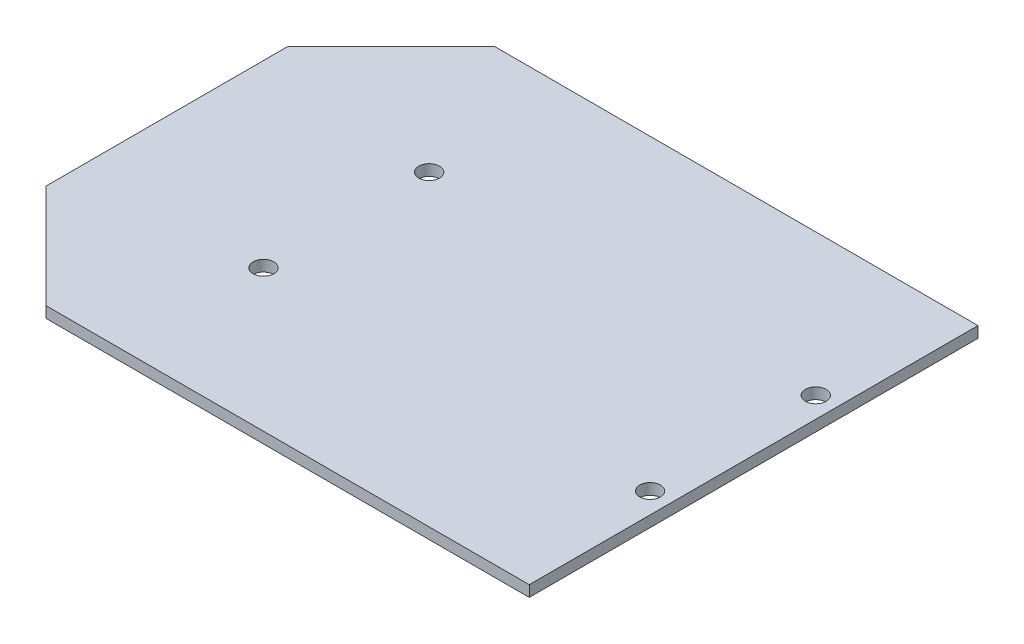
SolidWorks part; units mm, degrees
ref_plane "Front Plane" through (0, 0, 0) normal (0, 0, 1) x (1, 0, 0)
ref_plane "Top Plane" through (0, 0, 0) normal (0, 1, 0) x (1, 0, 0)
ref_plane "Right Plane" through (0, 0, 0) normal (1, 0, 0) x (0, 0, -1)
sketch "Sketch1" plane through (0, 0, 0) normal (0, 1, 0) x (1, 0, 0)
  line L1 (-42.5, -32.5) -> (42.5, -32.5)
  line L2 (-42.5, -32.5) -> (-42.5, 32.5)
  line L3 (-42.5, 32.5) -> (42.5, 32.5)
  line L4 (42.5, -32.5) -> (42.5, 32.5)
  line L5 (-42.5, -32.5) -> (42.5, 32.5) construction
  line L6 (-42.5, 32.5) -> (42.5, -32.5) construction
  point P0 (0, 0)
  dimension "D1" = 85
  dimension "D2" = 65
extrude "Boss-Extrude1" add sketch "Sketch1" along normal blind 1.6
sketch "Sketch3" plane through (0, 0, 0) normal (0, -1, 0) x (-1, 0, 0)
  line L0 (42.5, 32.5) -> (42.5, 17.5)
  line L1 (42.5, 32.5) -> (42.5, -32.5) construction
  line L2 (42.5, 17.5) -> (27.5, 32.5)
  line L3 (-42.5, 32.5) -> (42.5, 32.5) construction
  line L4 (27.5, 32.5) -> (42.5, 32.5)
  line L5 (35, 25) -> (57.93, 47.93) construction
  line L6 (0, 0) -> (64.2527, 0) construction
  line L7 (27.5, -32.5) -> (42.5, -32.5)
  line L8 (42.5, -17.5) -> (27.5, -32.5)
  line L9 (42.5, -32.5) -> (42.5, -17.5)
  dimension "D1" = 15
  dimension "D2" = 15
  dimension "D3" = 45
extrude "Cut-Extrude1" cut sketch "Sketch3" against normal blind 10
sketch "Sketch4" plane through (0, 0, 0) normal (0, -1, 0) x (-1, 0, 0)
  line L0 (42.5, 17.5) -> (42.5, -17.5) construction
  line L1 (27.5, -32.5) -> (-42.5, -32.5) construction
  line L2 (42.5, 0) -> (0, 0) construction
  circle A4 centre (16.5, -12) radius 1.5
  circle A6 centre (16.5, 12) radius 1.5
  circle A7 centre (-39.5, -12) radius 1.5
  circle A8 centre (-39.5, 12) radius 1.5
  dimension "D1" = 3
  dimension "D2" = 3
  dimension "D3" = 26
  dimension "D4" = 20.5
  dimension "D5" = 3
extrude "Cut-Extrude2" cut sketch "Sketch4" against normal blind 16
